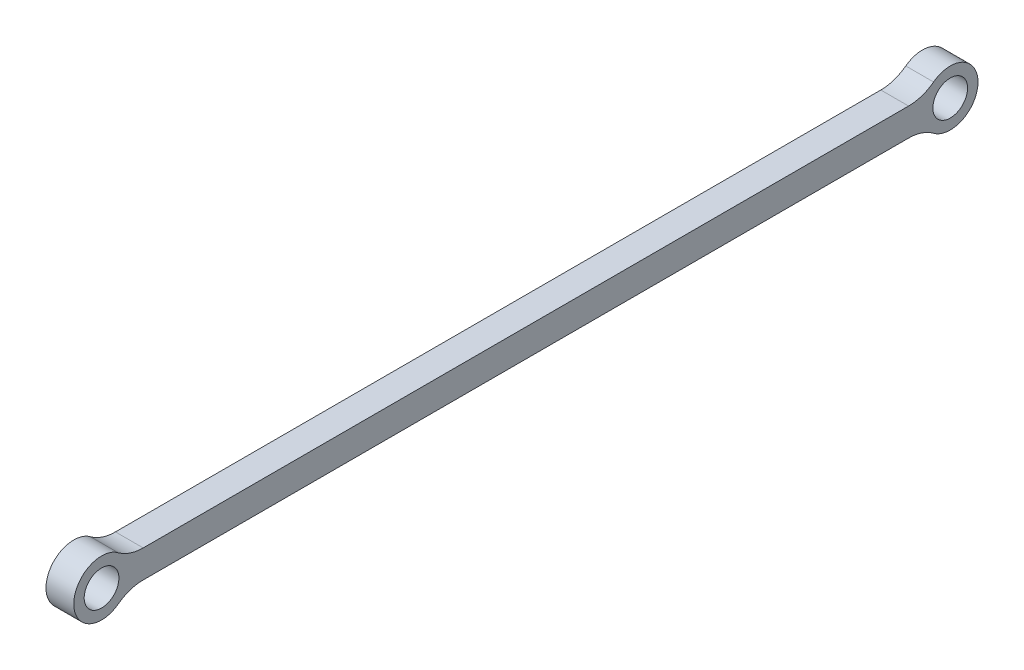
SolidWorks part; units mm, degrees
material "Thornel Mat VMA"
ref_plane "前视基准面" through (0, 0, 0) normal (0, 0, 1) x (1, 0, 0)
ref_plane "上视基准面" through (0, 0, 0) normal (0, 1, 0) x (1, 0, 0)
ref_plane "右视基准面" through (0, 0, 0) normal (1, 0, 0) x (0, 0, -1)
sketch "草图1" plane through (0, 0, 0) normal (1, 0, 0) x (0, 0, -1)
  line L0 (0, 0) -> (244.5, 0) construction
  line L1 (0, 8) -> (244.5, 8)
  line L2 (0, -8) -> (244.5, -8)
  arc A0 (0, 8) -> (0, -8) centre (0, 0) ccw
  arc A1 (244.5, -8) -> (244.5, 8) centre (244.5, 0) ccw
  circle A2 centre (244.5, 0) radius 5
  circle A3 centre (0, 0) radius 5
  point P3 (122.25, 0)
  dimension "D1" = 10
  dimension "D2" = 10
  dimension "D3" = 16
  dimension "D4" = 244.5
extrude "凸台-拉伸1" add sketch "草图1" along normal blind 8
sketch "草图2" plane through (8, 0, 0) normal (1, 0, 0) x (0, 0, -1)
  line L0 (0, 0) -> (244.5, 0) construction
  line L1 (0, -8) -> (244.5, -8) construction
  line L2 (244.5, 8) -> (0, 8) construction
  line L3 (237.5718, -4) -> (6.9282, -4)
  line L4 (237.5718, 4) -> (6.9282, 4)
  line L5 (0, -8) -> (244.5, -8)
  line L6 (244.5, 8) -> (0, 8)
  arc A0 (0, -8) -> (6.9282, -4) centre (0, 0) ccw
  arc A1 (0, 8) -> (0, -8) centre (0, 0) ccw construction
  arc A2 (244.5, 8) -> (237.5718, 4) centre (244.5, 0) ccw
  arc A3 (6.9282, 4) -> (0, 8) centre (0, 0) ccw
  arc A4 (237.5718, -4) -> (244.5, -8) centre (244.5, 0) ccw
  dimension "D1" = 8
extrude "切除-拉伸1" cut sketch "草图2" against normal through all
fillet "圆角1" radius 12 4 edges at (4, -4, -237.5718) (4, 4, -6.9282) (4, -4, -6.9282) (4, 4, -237.5718)
sketch "草图4" plane through (8, 0, 0) normal (1, 0, 0) x (0, 0, -1)
  line L0 (0, 0) -> (244.5, 0) construction
  line L1 (122.25, 0) -> (122.25, 19.2035) construction
  line L2 (12, 4) -> (232.5, 4) construction
  line L6 (121.75, 2.2) -> (109.75, 2.2)
  line L9 (121.75, 2.2) -> (121.75, -2.2)
  line L12 (121.75, -2.2) -> (109.75, -2.2)
  line L15 (109.75, 2.2) -> (109.75, -2.2)
  line L18 (121.75, 2.2) -> (109.75, -2.2) construction
  line L21 (214.75, -2.2) -> (200.75, 2.2) construction
  line L24 (121.75, -2.2) -> (109.75, 2.2) construction
  line L27 (108.75, 2.2) -> (96.75, 2.2)
  line L30 (96.75, 2.2) -> (96.75, -2.2)
  line L33 (108.75, 2.2) -> (108.75, -2.2)
  line L36 (108.75, -2.2) -> (96.75, -2.2)
  line L39 (95.75, 2.2) -> (83.75, 2.2)
  line L46 (83.75, 2.2) -> (83.75, -2.2)
  line L47 (95.75, 2.2) -> (95.75, -2.2)
  line L48 (95.75, -2.2) -> (83.75, -2.2)
  line L49 (82.75, 2.2) -> (70.75, 2.2)
  line L50 (70.75, 2.2) -> (70.75, -2.2)
  line L51 (82.75, 2.2) -> (82.75, -2.2)
  line L52 (82.75, -2.2) -> (70.75, -2.2)
  line L53 (69.75, 2.2) -> (57.75, 2.2)
  line L54 (57.75, 2.2) -> (57.75, -2.2)
  line L55 (69.75, 2.2) -> (69.75, -2.2)
  line L56 (69.75, -2.2) -> (57.75, -2.2)
  line L57 (56.75, 2.2) -> (44.75, 2.2)
  line L58 (44.75, 2.2) -> (44.75, -2.2)
  line L59 (56.75, 2.2) -> (56.75, -2.2)
  line L60 (56.75, -2.2) -> (44.75, -2.2)
  line L61 (29.75, 2.2) -> (43.75, 2.2)
  line L62 (29.75, 2.2) -> (29.75, -2.2)
  line L63 (29.75, -2.2) -> (43.75, -2.2)
  line L64 (43.75, 2.2) -> (43.75, -2.2)
  line L65 (29.75, 2.2) -> (43.75, -2.2) construction
  line L66 (29.75, -2.2) -> (43.75, 2.2) construction
  line L67 (214.75, 2.2) -> (200.75, -2.2) construction
  line L68 (122.75, -2.2) -> (134.75, 2.2) construction
  line L69 (122.75, 2.2) -> (134.75, -2.2) construction
  line L70 (200.75, 2.2) -> (200.75, -2.2)
  line L71 (214.75, -2.2) -> (200.75, -2.2)
  line L72 (214.75, 2.2) -> (214.75, -2.2)
  line L73 (214.75, 2.2) -> (200.75, 2.2)
  line L74 (187.75, -2.2) -> (199.75, -2.2)
  line L75 (187.75, 2.2) -> (187.75, -2.2)
  line L76 (199.75, 2.2) -> (199.75, -2.2)
  line L77 (187.75, 2.2) -> (199.75, 2.2)
  line L78 (174.75, -2.2) -> (186.75, -2.2)
  line L79 (174.75, 2.2) -> (174.75, -2.2)
  line L80 (186.75, 2.2) -> (186.75, -2.2)
  line L81 (174.75, 2.2) -> (186.75, 2.2)
  line L82 (161.75, -2.2) -> (173.75, -2.2)
  line L83 (161.75, 2.2) -> (161.75, -2.2)
  line L84 (173.75, 2.2) -> (173.75, -2.2)
  line L85 (161.75, 2.2) -> (173.75, 2.2)
  line L86 (148.75, -2.2) -> (160.75, -2.2)
  line L87 (148.75, 2.2) -> (148.75, -2.2)
  line L88 (160.75, 2.2) -> (160.75, -2.2)
  line L89 (148.75, 2.2) -> (160.75, 2.2)
  line L90 (135.75, -2.2) -> (147.75, -2.2)
  line L91 (135.75, 2.2) -> (135.75, -2.2)
  line L92 (147.75, 2.2) -> (147.75, -2.2)
  line L93 (135.75, 2.2) -> (147.75, 2.2)
  line L94 (134.75, 2.2) -> (134.75, -2.2)
  line L95 (122.75, -2.2) -> (134.75, -2.2)
  line L96 (122.75, 2.2) -> (122.75, -2.2)
  line L97 (122.75, 2.2) -> (134.75, 2.2)
  point P6 (115.75, 0)
  point P13 (36.75, 0)
  point P66 (207.75, 0)
  point P67 (128.75, 0)
  dimension "D2" = 1.8
  dimension "D3" = 12
  dimension "D5" = 13
  dimension "D6" = 1
  dimension "D7" = 14
  dimension "D1" = 0.5
  dimension "D4" = 6
extrude "切除-拉伸2" [suppressed] cut sketch "草图4" against normal through all
fillet "圆角2" [suppressed] radius 1.5
sketch "草图5" plane through (8, 0, 0) normal (1, 0, 0) x (0, 0, -1)
  circle A0 centre (0, 0) radius 16.9196
sketch "草图6" plane through (8, 0, 0) normal (1, 0, 0) x (0, 0, -1)
  line L0 (244.5, 0) -> (122, 0) construction
  circle A0 centre (122, 0) radius 2.5
  circle A1 centre (0, 0) radius 5 construction
  dimension "D2" = 5
  dimension "D1" = 122
move or copy body "实体-移动/复制5" [suppressed] bodies to move or copy 107
move or copy body "实体-移动/复制6" [suppressed] bodies to move or copy 116
move or copy body "实体-移动/复制4" [suppressed] bodies to move or copy 107
move or copy body "实体-移动/复制3" [suppressed] bodies to move or copy 116
move or copy body "实体-移动/复制2" [suppressed] bodies to move or copy 107
move or copy body "实体-移动/复制1" [suppressed] bodies to move or copy 111
